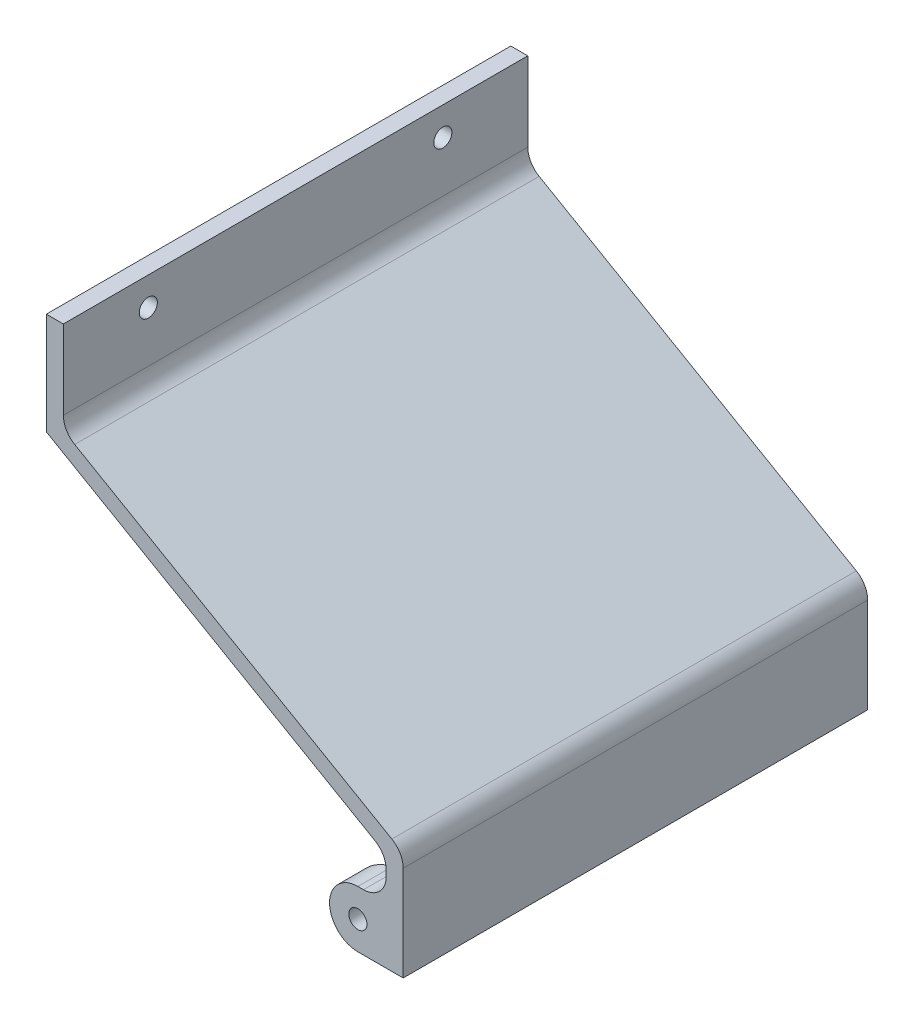
SolidWorks part; units mm, degrees
material "ABS"
ref_plane "前视基准面" through (0, 0, 0) normal (0, 0, 1) x (1, 0, 0)
ref_plane "上视基准面" through (0, 0, 0) normal (0, 1, 0) x (1, 0, 0)
ref_plane "右视基准面" through (0, 0, 0) normal (1, 0, 0) x (0, 0, -1)
sketch "草图1" plane through (0, 0, 0) normal (0, 0, 1) x (1, 0, 0)
  line L0 (-31.5, 18.1157) -> (28.5, -16.5253)
  line L1 (-31.5, 18.1157) -> (-31.5, 36.1157)
  line L2 (-31.5, 36.1157) -> (-28.5, 36.1157)
  line L3 (28.5, -16.5253) -> (28.5, -33.8843)
  line L4 (-28.5, 36.1157) -> (-28.5, 19.8477)
  line L5 (28.5, -13.0612) -> (-28.5, 19.8477)
  line L6 (28.5, -33.8843) -> (31.5, -33.8843)
  line L7 (31.5, -14.7933) -> (31.5, -33.8843)
  line L8 (28.5, -13.0612) -> (31.5, -14.7933)
  point P4 (28.5, -16.5253)
extrude "凸台-拉伸1" add sketch "草图1" along normal blind 82
sketch "草图2" plane through (-28.5, 0, 0) normal (1, 0, 0) x (0, 0, -1)
  line L0 (-82, 36.1157) -> (0, 36.1157) construction
  line L1 (-82, 19.8477) -> (-82, 36.1157) construction
  line L2 (-41, 19.8477) -> (-41, 27.3559) construction
  line L3 (-82, 19.8477) -> (0, 19.8477) construction
  circle A0 centre (-67, 31.1157) radius 1.6
  circle A1 centre (-15, 31.1157) radius 1.6
  dimension "D3" = 3.2
  dimension "D1" = 5
  dimension "D2" = 15
extrude "切除-拉伸1" cut sketch "草图2" against normal up to next
sketch "草图3" plane through (0, 0, 0) normal (0, 0, -1) x (-1, 0, 0)
  line L0 (-28.5, -33.8843) -> (-23.5, -33.8843)
  line L2 (-23.5, -23.8843) -> (-28.5, -23.8843)
  line L3 (-28.5, -16.5253) -> (-28.5, -33.8843) construction
  line L4 (-28.5, -23.8843) -> (-28.5, -33.8843)
  arc A0 (-23.5, -33.8843) -> (-23.5, -23.8843) centre (-23.5, -28.8843) ccw
  circle A1 centre (-23.5, -28.8843) radius 1.6
  dimension "D2" = 5
  dimension "D3" = 3.2
  dimension "D1" = 5
extrude "凸台-拉伸2" add sketch "草图3" against normal blind 10
sketch "草图4" plane through (0, -33.8843, 0) normal (0, -1, 0) x (1, 0, 0)
  line L0 (15.4893, 10) -> (15.4893, 5)
  line L1 (18.5, 10) -> (18.5, 0) construction
  line L2 (28.5, 10) -> (26.534, 6.6564) construction
  line L3 (26.534, 6.6564) -> (22.3204, 5.3795) construction
  line L5 (22.3204, 5.3795) -> (18.5, 5) construction
  line L6 (28.5, 10) -> (15.4893, 10)
  line L7 (15.4893, 5) -> (18.5, 5)
  spline S0 degree 3 poles (28.5, 10) (26.534, 6.6564) (22.3204, 5.3795) (18.5, 5) knots 0 0 0 0 1 1 1 1
extrude "切除-拉伸2" cut sketch "草图4" against normal up to surface (10 mm away) up to face at (26, -23.8843, 5)
sketch3d "3D草图1" plane through (0, 0, 0) normal (0, 0, 1) x (1, 0, 0)
  dimension "D1" = 5
sketch "草图5" plane through (0, 0, 5) normal (0, 0, -1) x (-1, 0, 0)
  circle A0 centre (-23.5, -28.8843) radius 3
  dimension "D1" = 6
extrude "切除-拉伸3" cut sketch "草图5" against normal blind 10
sketch "草图6" plane through (0, 0, 82) normal (0, 0, 1) x (1, 0, 0)
  line L0 (28.5, -23.8843) -> (23.5, -23.8843)
  line L1 (28.5, -23.8843) -> (23.5, -23.8843) construction
  line L3 (23.5, -33.8843) -> (28.5, -33.8843)
  line L4 (28.5, -33.8843) -> (28.5, -23.8843)
  arc A0 (23.5, -23.8843) -> (23.5, -33.8843) centre (23.5, -28.8843) ccw construction
  arc A1 (23.5, -23.8843) -> (23.5, -33.8843) centre (23.5, -28.8843) ccw
  circle A2 centre (23.5, -28.8843) radius 1.6
  dimension "D1" = 5
  dimension "D3" = 3.2
  dimension "D2" = 5
extrude "凸台-拉伸3" add sketch "草图6" against normal blind 10
sketch "草图7" plane through (0, -33.8843, 0) normal (0, -1, 0) x (1, 0, 0)
  line L1 (18.5, 82) -> (18.5, 72) construction
  line L5 (28.5, 72) -> (25.1857, 75.3884) construction
  line L6 (25.1857, 75.3884) -> (22.5787, 76.6602) construction
  line L8 (22.5787, 76.6602) -> (18.5, 77) construction
  line L9 (28.5, 72) -> (15.7113, 72)
  line L10 (15.7113, 72) -> (15.7113, 77)
  line L11 (15.7113, 77) -> (18.5, 77)
  spline S0 degree 3 poles (28.5, 72) (25.1857, 75.3884) (22.5787, 76.6602) (18.5, 77) knots 0 0 0 0 1 1 1 1
extrude "切除-拉伸4" cut sketch "草图7" against normal up to next
sketch3d "3D草图3" plane through (0, 0, 0) normal (0, 0, 1) x (1, 0, 0)
  dimension "D1" = 5
sketch "草图8" plane through (0, 0, 77) normal (0, 0, 1) x (1, 0, 0)
  circle A0 centre (23.5, -28.8843) radius 3
  dimension "D1" = 6
extrude "切除-拉伸5" cut sketch "草图8" against normal blind 10
fillet "圆角1" radius 4 5 edges at (28.5, -16.5253, 41) (31.5, -14.7933, 41) (-28.5, 19.8477, 41) (28.5, -23.8843, 5)
